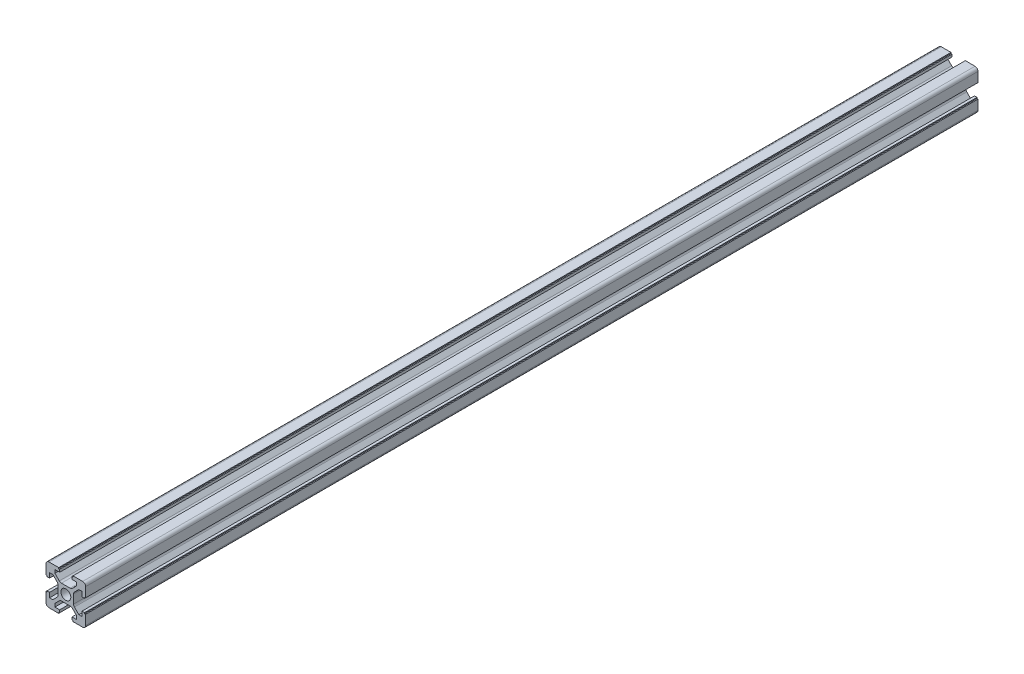
SolidWorks part; units mm, degrees
material "6061 合金"
ref_plane "前视基准面" through (0, 0, 0) normal (0, 0, 1) x (1, 0, 0)
ref_plane "上视基准面" through (0, 0, 0) normal (0, 1, 0) x (1, 0, 0)
ref_plane "右视基准面" through (0, 0, 0) normal (1, 0, 0) x (0, 0, -1)
sketch "草图1" plane through (0, 0, 0) normal (0, 0, 1) x (1, 0, 0)
  line L0 (-6.5607, 5.5) -> (-4.3393, 3.2787)
  line L1 (-3.9, 2.218) -> (-3.9, -2.218)
  line L2 (-4.3393, -3.2787) -> (-6.5607, -5.5)
  line L3 (-6.5607, -5.5) -> (-8.2, -5.5)
  line L4 (-8.2, -5.5) -> (-8.2, -3.1)
  line L5 (-8.2, -3.1) -> (-9.5, -3.1)
  line L6 (-9.5, -3.1) -> (-9.5, -3.6)
  line L7 (-9.5, -3.6) -> (-10, -3.6)
  line L8 (-10, -3.6) -> (-10, -8.5)
  line L9 (-6.5607, 5.5) -> (-8.2, 5.5)
  line L10 (-8.2, 5.5) -> (-8.2, 3.1)
  line L11 (-8.2, 3.1) -> (-9.5, 3.1)
  line L12 (-9.5, 3.1) -> (-9.5, 3.6)
  line L13 (-9.5, 3.6) -> (-10, 3.6)
  line L14 (-10, 3.6) -> (-10, 8.5)
  line L15 (5.5, 6.5607) -> (3.2787, 4.3393)
  line L16 (2.218, 3.9) -> (-2.218, 3.9)
  line L17 (-3.2787, 4.3393) -> (-5.5, 6.5607)
  line L18 (-5.5, 6.5607) -> (-5.5, 8.2)
  line L19 (-5.5, 8.2) -> (-3.1, 8.2)
  line L20 (-3.1, 8.2) -> (-3.1, 9.5)
  line L21 (-3.1, 9.5) -> (-3.6, 9.5)
  line L22 (-3.6, 9.5) -> (-3.6, 10)
  line L23 (-3.6, 10) -> (-8.5, 10)
  line L24 (5.5, 6.5607) -> (5.5, 8.2)
  line L25 (5.5, 8.2) -> (3.1, 8.2)
  line L26 (3.1, 8.2) -> (3.1, 9.5)
  line L27 (3.1, 9.5) -> (3.6, 9.5)
  line L28 (3.6, 9.5) -> (3.6, 10)
  line L29 (3.6, 10) -> (8.5, 10)
  line L30 (6.5607, -5.5) -> (4.3393, -3.2787)
  line L31 (3.9, -2.218) -> (3.9, 2.218)
  line L32 (4.3393, 3.2787) -> (6.5607, 5.5)
  line L33 (6.5607, 5.5) -> (8.2, 5.5)
  line L34 (8.2, 5.5) -> (8.2, 3.1)
  line L35 (8.2, 3.1) -> (9.5, 3.1)
  line L36 (9.5, 3.1) -> (9.5, 3.6)
  line L37 (9.5, 3.6) -> (10, 3.6)
  line L38 (10, 3.6) -> (10, 8.5)
  line L39 (6.5607, -5.5) -> (8.2, -5.5)
  line L40 (8.2, -5.5) -> (8.2, -3.1)
  line L41 (8.2, -3.1) -> (9.5, -3.1)
  line L42 (9.5, -3.1) -> (9.5, -3.6)
  line L43 (9.5, -3.6) -> (10, -3.6)
  line L44 (10, -3.6) -> (10, -8.5)
  line L45 (-5.5, -6.5607) -> (-3.2787, -4.3393)
  line L46 (-2.218, -3.9) -> (2.218, -3.9)
  line L47 (3.2787, -4.3393) -> (5.5, -6.5607)
  line L48 (5.5, -6.5607) -> (5.5, -8.2)
  line L49 (5.5, -8.2) -> (3.1, -8.2)
  line L50 (3.1, -8.2) -> (3.1, -9.5)
  line L51 (3.1, -9.5) -> (3.6, -9.5)
  line L52 (3.6, -9.5) -> (3.6, -10)
  line L53 (3.6, -10) -> (8.5, -10)
  line L54 (-5.5, -6.5607) -> (-5.5, -8.2)
  line L55 (-5.5, -8.2) -> (-3.1, -8.2)
  line L56 (-3.1, -8.2) -> (-3.1, -9.5)
  line L57 (-3.1, -9.5) -> (-3.6, -9.5)
  line L58 (-3.6, -9.5) -> (-3.6, -10)
  line L59 (-3.6, -10) -> (-8.5, -10)
  line L60 (0, 0) -> (-3.9, 2.8393) construction
  line L61 (0, 0) -> (2.8393, 3.9) construction
  arc A0 (4.3393, -3.2787) -> (3.9, -2.218) centre (5.4, -2.218) cw
  arc A1 (3.9, 2.218) -> (4.3393, 3.2787) centre (5.4, 2.218) cw
  arc A2 (3.2787, 4.3393) -> (2.218, 3.9) centre (2.218, 5.4) cw
  arc A3 (-2.218, 3.9) -> (-3.2787, 4.3393) centre (-2.218, 5.4) cw
  arc A4 (-4.3393, 3.2787) -> (-3.9, 2.218) centre (-5.4, 2.218) cw
  arc A5 (-3.9, -2.218) -> (-4.3393, -3.2787) centre (-5.4, -2.218) cw
  arc A6 (2.218, -3.9) -> (3.2787, -4.3393) centre (2.218, -5.4) cw
  arc A7 (-3.2787, -4.3393) -> (-2.218, -3.9) centre (-2.218, -5.4) cw
  arc A8 (-10, -8.5) -> (-8.5, -10) centre (-8.5, -8.5) ccw
  arc A9 (10, -8.5) -> (8.5, -10) centre (8.5, -8.5) cw
  arc A10 (8.5, 10) -> (10, 8.5) centre (8.5, 8.5) cw
  arc A11 (-10, 8.5) -> (-8.5, 10) centre (-8.5, 8.5) cw
  circle A12 centre (0, 0) radius 2.5
  point P27 (-3.9, 0)
  point P75 (2.8393, 3.9)
  dimension "D12" = 1.5
  dimension "D13" = 5
  dimension "D2" = 20
  dimension "D3" = 7.2
  dimension "D4" = 6.2
  dimension "D5" = 7.8
  dimension "D6" = 45
  dimension "D7" = 1.5
  dimension "D8" = 11
  dimension "D9" = 1.8
  dimension "D10" = 0.5
  dimension "D11" = 3.1
  dimension "D1" = 4
extrude "凸台-拉伸1" add sketch "草图1" along normal mid plane 450
